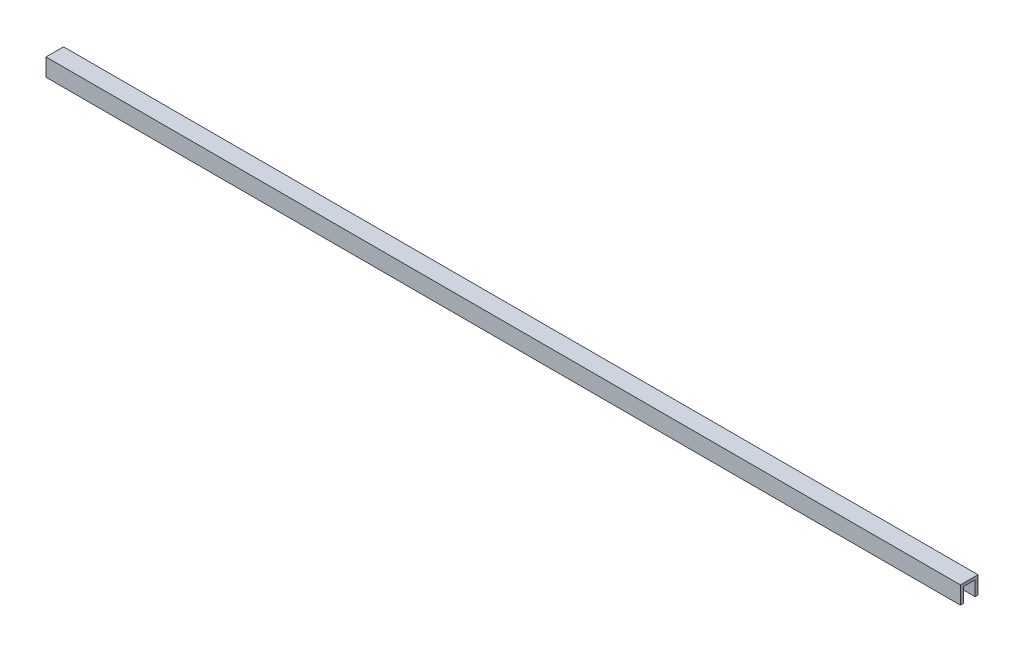
SolidWorks part; units mm, degrees
material "6063-T6"
ref_plane "Front Plane" through (0, 0, 0) normal (0, 0, 1) x (1, 0, 0)
ref_plane "Top Plane" through (0, 0, 0) normal (0, 1, 0) x (1, 0, 0)
ref_plane "Right Plane" through (0, 0, 0) normal (1, 0, 0) x (0, 0, -1)
sketch "Sketch1" plane through (0, 0, 0) normal (1, 0, 0) x (0, 0, -1)
  line L0 (0, -19.05) -> (0, 0)
  line L1 (0, 0) -> (19.05, 0)
  line L2 (19.05, 0) -> (19.05, -19.05)
  line L3 (3.175, -19.05) -> (3.175, -3.175)
  line L4 (3.175, -3.175) -> (15.875, -3.175)
  line L5 (15.875, -3.175) -> (15.875, -19.05)
  line L6 (0, -19.05) -> (3.175, -19.05)
  line L7 (19.05, -19.05) -> (15.875, -19.05)
  dimension "D1" = 19.05
  dimension "D2" = 3.175
extrude "Boss-Extrude1" add sketch "Sketch1" along normal blind 990.6
